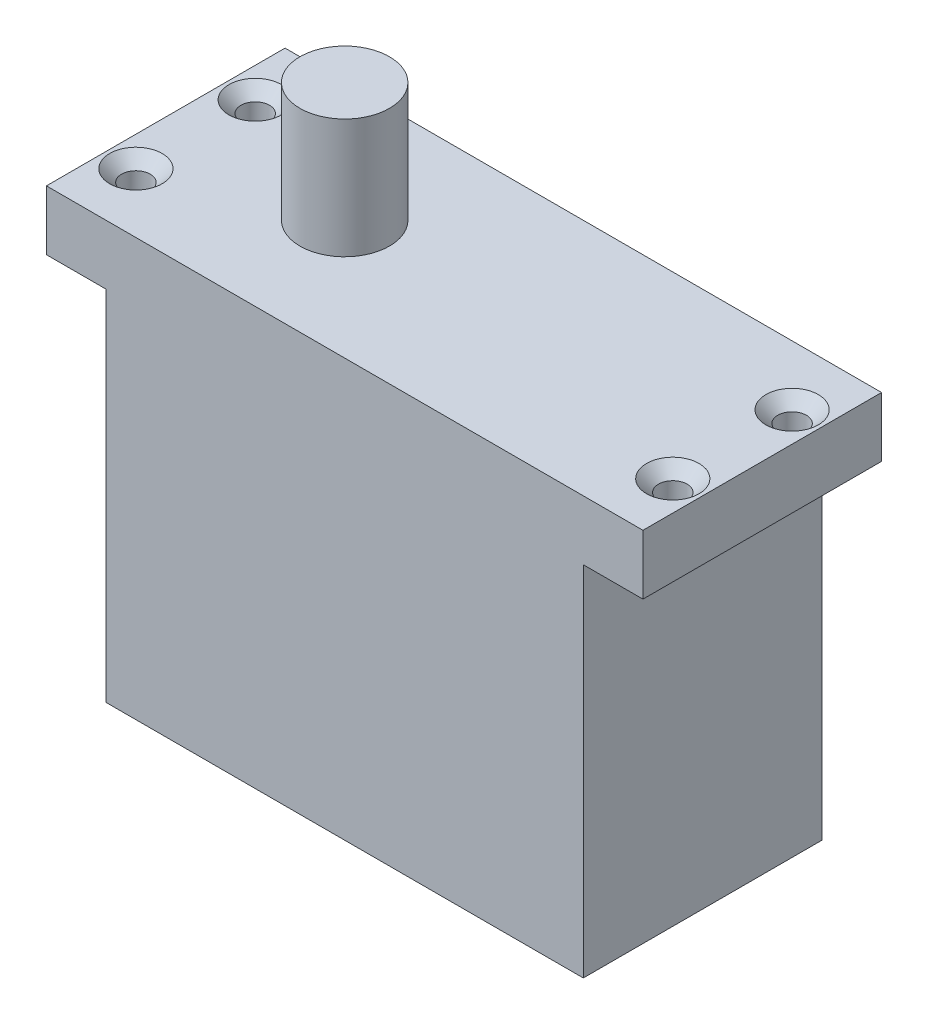
SolidWorks part; units mm, degrees
ref_plane "Front Plane" through (0, 0, 0) normal (0, 0, 1) x (1, 0, 0)
ref_plane "Top Plane" through (0, 0, 0) normal (0, 1, 0) x (1, 0, 0)
ref_plane "Right Plane" through (0, 0, 0) normal (1, 0, 0) x (0, 0, -1)
sketch "Sketch1" plane through (0, 0, 0) normal (0, 1, 0) x (1, 0, 0)
  line L1 (-20, 10) -> (20, 10)
  line L2 (-20, 10) -> (-20, -10)
  line L3 (-20, -10) -> (20, -10)
  line L4 (20, 10) -> (20, -10)
  line L5 (-20, 10) -> (20, -10) construction
  line L6 (-20, -10) -> (20, 10) construction
  point P0 (0, 0)
  dimension "D1" = 20
  dimension "D2" = 40
extrude "Boss-Extrude1" add sketch "Sketch1" along normal blind 35
sketch "Sketch2" plane through (0, 35, 0) normal (0, 1, 0) x (1, 0, 0)
  line L4 (-20, -10) -> (-25, -10)
  line L5 (-20, -10) -> (-20, 10)
  line L6 (-20, 10) -> (-25, 10)
  line L7 (-25, -10) -> (-25, 10)
  line L8 (20, -10) -> (25, -10)
  line L9 (20, -10) -> (20, 10)
  line L10 (20, 10) -> (25, 10)
  line L11 (25, -10) -> (25, 10)
  dimension "D2" = 5
  dimension "D3" = 5
extrude "Boss-Extrude2" add sketch "Sketch2" against normal blind 5 contours L4 L7 L6 L5 | L11 L10 L9 L8
sketch "Sketch3" plane through (0, 35, 0) normal (0, 1, 0) x (1, 0, 0)
  line L0 (-25, 0) -> (-10, 0) construction
  line L1 (-25, -10) -> (-25, 10) construction
  circle A0 centre (-10, 0) radius 3.75
  dimension "D2" = 7.5
  dimension "D1" = 15
extrude "Boss-Extrude3" add sketch "Sketch3" along normal blind 10
sketch "Sketch8" plane through (0, 35, 0) normal (0, 1, 0) x (1, 0, 0)
  line L0 (25, 0) -> (20, 0) construction
  line L1 (25, -10) -> (25, 10) construction
  line L2 (22.5, -5) -> (22.5, 5)
  point P8 (22.5, 0)
  dimension "D1" = 5
  dimension "D2" = 10
hole_wizard "CSK for M2 Flat Head Machine Screw2" positions "Sketch11" profile "Sketch12" countersink size "M2" standard "ANSI Metric" end condition through all
sketch "Sketch11" plane through (0, 35, 0) normal (0, 1, 0) x (1, 0, 0)
  point P0 (22.5, -5)
  point P3 (22.5, 5)
sketch "Sketch12" plane through (22.5, 35, 5) normal (1, 0, 0) x (0, 0, 1)
  line L0 (0, 0) -> (0, 35)
  line L1 (0, 35) -> (1.2, 35)
  line L2 (1.2, 35) -> (1.2, 1)
  line L3 (1.2, 1) -> (2.2, 0)
  line L5 (2.2, 0) -> (0, 0)
  line L6 (-1.2, 1) -> (-2.2, 0) construction
  line L11 (0, -6.35) -> (0, 107.95) construction
  dimension "Thru Hole Dia." = 2.4
  dimension "Thru Hole Depth" = 35
  dimension "Near C'Sink Dia." = 4.4
  dimension "Near C'Sink Angle" = 90
mirror "Mirror1" about plane through (0, 0, 0) normal (1, 0, 0) of "CSK for M2 Flat Head Machine Screw2"
